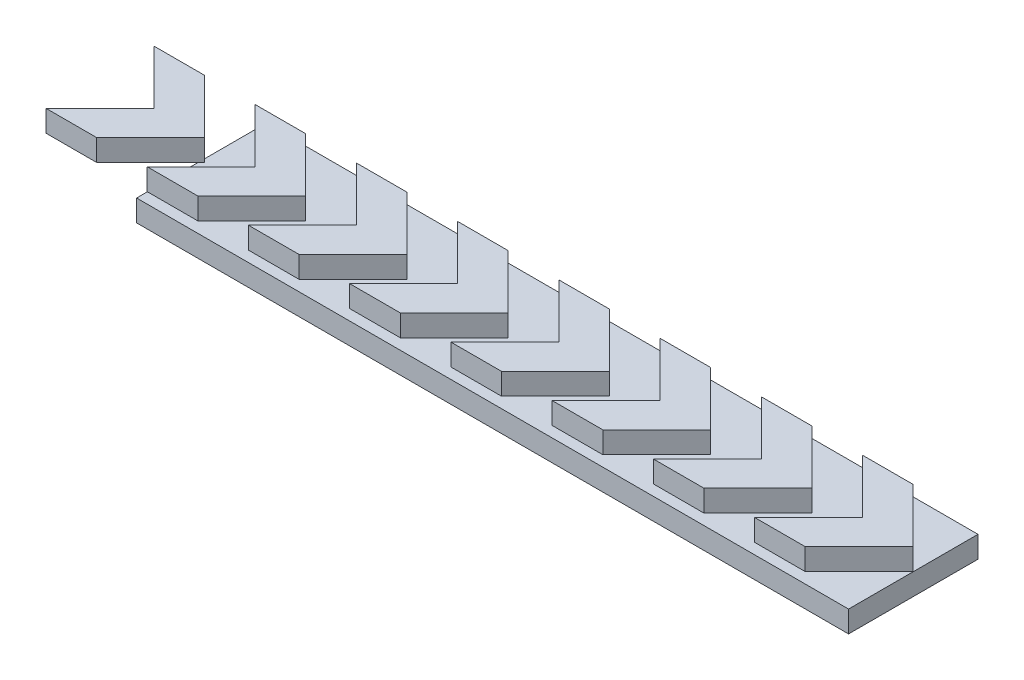
SolidWorks part; units mm, degrees
ref_plane "Front Plane" through (0, 0, 0) normal (0, 0, 1) x (1, 0, 0)
ref_plane "Top Plane" through (0, 0, 0) normal (0, 1, 0) x (1, 0, 0)
ref_plane "Right Plane" through (0, 0, 0) normal (1, 0, 0) x (0, 0, -1)
sketch "Sketch1" plane through (0, 0, 0) normal (0, 1, 0) x (1, 0, 0)
  line L1 (-165, -30) -> (165, -30)
  line L2 (-165, -30) -> (-165, 30)
  line L3 (-165, 30) -> (165, 30)
  line L4 (165, -30) -> (165, 30)
  line L5 (-165, -30) -> (165, 30) construction
  line L6 (-165, 30) -> (165, -30) construction
  point P0 (0, 0)
  dimension "D1" = 330
  dimension "D2" = 60
extrude "Boss-Extrude1" add sketch "Sketch1" along normal blind 10
sketch "Sketch2" plane through (0, 10, 0) normal (0, 1, 0) x (1, 0, 0)
  line L0 (-165, 30) -> (-212, 30) construction
  line L1 (-212, 30) -> (-212, 25) construction
  line L2 (-212, 25) -> (-187, 0)
  line L3 (-187, 0) -> (-212, -25)
  line L4 (-212, -25) -> (-188.5385, -25)
  line L5 (-188.5385, -25) -> (-163.5385, 0)
  line L6 (-163.5385, 0) -> (-188.5385, 25)
  line L7 (-188.5385, 25) -> (-212, 25)
  line L8 (-212, -25) -> (-212, 25) construction
  line L9 (-187, 0) -> (-163.5385, 0) construction
  line L10 (-188.5385, -25) -> (-188.5385, -30) construction
  line L11 (-165, -30) -> (165, -30) construction
  line L12 (-141.6154, 25) -> (-165.0769, 25)
  line L13 (-165.0769, 25) -> (-140.0769, 0)
  line L14 (-140.0769, 0) -> (-165.0769, -25)
  line L15 (-165.0769, -25) -> (-141.6154, -25)
  line L16 (-141.6154, -25) -> (-116.6154, 0)
  line L17 (-116.6154, 0) -> (-141.6154, 25)
  line L18 (-94.6923, 25) -> (-118.1538, 25)
  line L19 (-118.1538, 25) -> (-93.1538, 0)
  line L20 (-93.1538, 0) -> (-118.1538, -25)
  line L21 (-118.1538, -25) -> (-94.6923, -25)
  line L22 (-94.6923, -25) -> (-69.6923, 0)
  line L23 (-69.6923, 0) -> (-94.6923, 25)
  line L24 (-47.7692, 25) -> (-71.2308, 25)
  line L25 (-71.2308, 25) -> (-46.2308, 0)
  line L26 (-46.2308, 0) -> (-71.2308, -25)
  line L27 (-71.2308, -25) -> (-47.7692, -25)
  line L28 (-47.7692, -25) -> (-22.7692, 0)
  line L29 (-22.7692, 0) -> (-47.7692, 25)
  line L30 (-0.8462, 25) -> (-24.3077, 25)
  line L31 (-24.3077, 25) -> (0.6923, 0)
  line L32 (0.6923, 0) -> (-24.3077, -25)
  line L33 (-24.3077, -25) -> (-0.8462, -25)
  line L34 (-0.8462, -25) -> (24.1538, 0)
  line L35 (24.1538, 0) -> (-0.8462, 25)
  line L36 (46.0769, 25) -> (22.6154, 25)
  line L37 (22.6154, 25) -> (47.6154, 0)
  line L38 (47.6154, 0) -> (22.6154, -25)
  line L39 (22.6154, -25) -> (46.0769, -25)
  line L40 (46.0769, -25) -> (71.0769, 0)
  line L41 (71.0769, 0) -> (46.0769, 25)
  line L42 (93, 25) -> (69.5385, 25)
  line L43 (69.5385, 25) -> (94.5385, 0)
  line L44 (94.5385, 0) -> (69.5385, -25)
  line L45 (69.5385, -25) -> (93, -25)
  line L46 (93, -25) -> (118, 0)
  line L47 (118, 0) -> (93, 25)
  line L48 (139.9231, 25) -> (116.4615, 25)
  line L49 (116.4615, 25) -> (141.4615, 0)
  line L50 (141.4615, 0) -> (116.4615, -25)
  line L51 (116.4615, -25) -> (139.9231, -25)
  line L52 (139.9231, -25) -> (164.9231, 0)
  line L53 (164.9231, 0) -> (139.9231, 25)
  line L54 (-188.5385, 25) -> (-165.0769, 25) construction
  point P4 (-157.9411, 0)
  point P13 (-171.2723, 0)
  point P56 (0, 0)
  point P57 (-166.0641, 0)
  point P58 (0, 0)
  dimension "D1" = 5
  dimension "D2" = 8
  dimension "D3" = 330
  dimension "D4" = 47
extrude "Boss-Extrude2" add sketch "Sketch2" along normal blind 10 separate body
equation "\"D4\" = 47"
